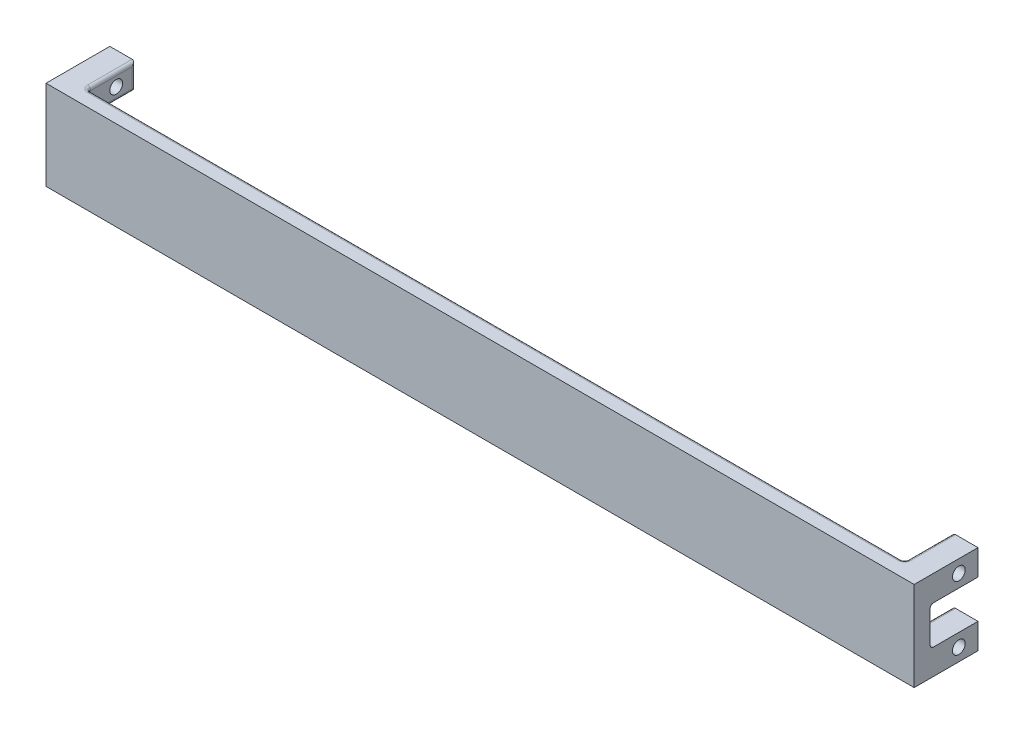
SolidWorks part; units mm, degrees
ref_plane "Front Plane" through (0, 0, 0) normal (0, 0, 1) x (1, 0, 0)
ref_plane "Top Plane" through (0, 0, 0) normal (0, 1, 0) x (1, 0, 0)
ref_plane "Right Plane" through (0, 0, 0) normal (1, 0, 0) x (0, 0, -1)
sketch "Sketch1" plane through (0, 0, 0) normal (0, 1, 0) x (1, 0, 0)
  line L1 (-136, -2.5) -> (136, -2.5)
  line L2 (-136, -2.5) -> (-136, 2.5)
  line L3 (-136, 2.5) -> (136, 2.5)
  line L4 (136, -2.5) -> (136, 2.5)
  line L5 (-136, -2.5) -> (136, 2.5) construction
  line L6 (-136, 2.5) -> (136, -2.5) construction
  point P0 (0, 0)
  dimension "D1" = 272
  dimension "D2" = 5
extrude "Boss-Extrude1" add sketch "Sketch1" along normal blind 28
sketch "Sketch2" plane through (0, 0, -2.5) normal (0, 0, -1) x (-1, 0, 0)
  line L0 (-136, 0) -> (136, 0) construction
  line L1 (-136, 28) -> (-128, 28)
  line L2 (-136, 28) -> (-136, 0)
  line L3 (-136, 0) -> (-128, 0)
  line L4 (-128, 28) -> (-128, 0)
  line L6 (136, 28) -> (128, 28)
  line L7 (136, 28) -> (136, 0)
  line L8 (136, 0) -> (128, 0)
  line L9 (128, 28) -> (128, 0)
  dimension "D1" = 8
  dimension "D2" = 8
extrude "Boss-Extrude2" add sketch "Sketch2" along normal blind 15
sketch "Sketch3" plane through (136, 0, 0) normal (1, 0, 0) x (0, 0, -1)
  line L0 (-2.5, 28) -> (-2.5, 0) construction
  line L1 (-2.5, 20) -> (17.5, 20)
  line L2 (-2.5, 20) -> (-2.5, 8)
  line L3 (-2.5, 8) -> (17.5, 8)
  line L4 (17.5, 20) -> (17.5, 8)
  line L5 (17.5, 28) -> (17.5, 0) construction
  line L6 (-2.5, 28) -> (17.5, 28) construction
  line L7 (-2.5, 0) -> (17.5, 0) construction
  line L9 (-2.5, 20) -> (2.5, 20)
  line L10 (-2.5, 20) -> (-2.5, 8)
  line L11 (-2.5, 8) -> (2.5, 8)
  line L12 (2.5, 20) -> (2.5, 8)
  line M4 (17.5, 0) -> (17.5, 28)
  dimension "D1" = 8
  dimension "D2" = 8
  dimension "D3" = 5
extrude "Cut-Extrude1" cut sketch "Sketch3" against normal through all both and the other way through all contours L1 L12 L3 M4
fillet "Fillet1" radius 1 22 edges at (-132, 8, -2.5) (-132, 20, -2.5) (132, 20, -2.5) (132, 8, -2.5) (-128, 8, -10) (-128, 20, -10) (128, 20, -10) (128, 8, -10) (-128, 4, -17.5) (-128, 4, -2.5) (-128, 24, -17.5) (-128, 24, -2.5) (128, 4, -2.5) (128, 4, -17.5) (128, 24, -2.5) (128, 24, -17.5) (128, 0, -10) (-128, 0, -10) (128, 28, -10) (-128, 28, -10) (0, 0, -2.5) (0, 28, -2.5)
sketch "Sketch4" plane through (136, 0, 0) normal (1, 0, 0) x (0, 0, -1)
  line L0 (-2.5, 28) -> (-2.5, 0) construction
  line L1 (17.5, 20) -> (3.5, 20) construction
  line L2 (17.5, 8) -> (3.5, 8) construction
  circle A0 centre (11.5, 24) radius 2
  circle A1 centre (11.5, 4) radius 2
  dimension "D1" = 4
  dimension "D2" = 4
  dimension "D3" = 14
  dimension "D4" = 14
  dimension "D5" = 4
  dimension "D6" = 4
extrude "Cut-Extrude2" cut sketch "Sketch4" against normal through all both and the other way through all
